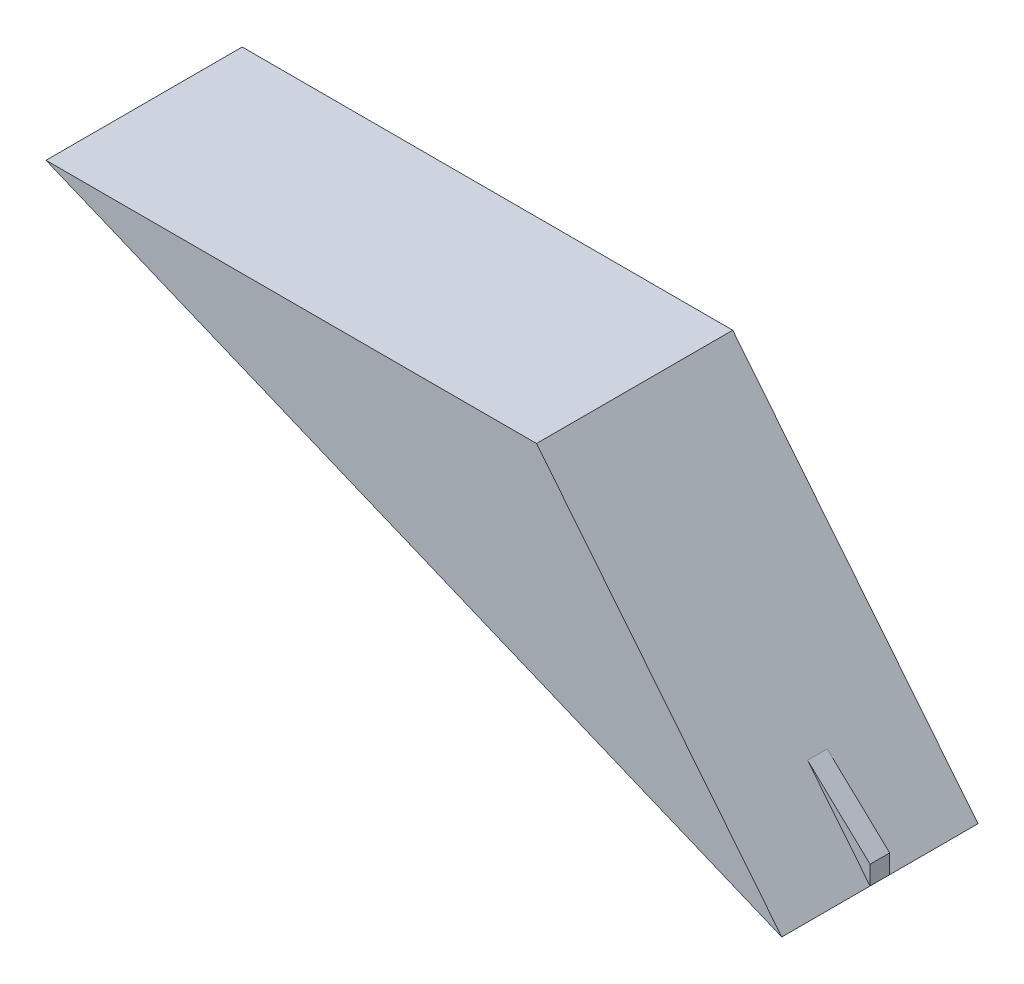
SolidWorks part; units mm, degrees
ref_plane "Front Plane" through (0, 0, 0) normal (0, 0, 1) x (1, 0, 0)
ref_plane "Top Plane" through (0, 0, 0) normal (0, 1, 0) x (1, 0, 0)
ref_plane "Right Plane" through (0, 0, 0) normal (1, 0, 0) x (0, 0, -1)
sketch "Sketch1" plane through (0, 0, 0) normal (0, 0, 1) x (1, 0, 0)
  line L0 (0, 0) -> (500, 0)
  line L3 (500, 0) -> (750, -310.6602)
  line L4 (0, 0) -> (750, -310.6602)
  dimension "D1" = 500
  dimension "D2" = 157.5
  dimension "D3" = 250
extrude "Boss-Extrude1" add sketch "Sketch1" along normal mid plane 200
sketch "Sketch2" plane through (0, 0, 0) normal (0, 0, 1) x (1, 0, 0)
  line L0 (686.2738, -284.2639) -> (686.2738, -231.4714)
  line L1 (0, 0) -> (750, -310.6602) construction
  line L2 (750, -310.6602) -> (500, 0) construction
  line L3 (686.2738, -231.4714) -> (750, -291.4088)
  line L4 (750, -291.4088) -> (750, -310.6602)
  line L5 (750, -310.6602) -> (686.2738, -284.2639)
  point P6 (750, -291.4088)
  point P10 (0, 0)
extrude "Boss-Extrude2" add sketch "Sketch2" along normal mid plane 20
